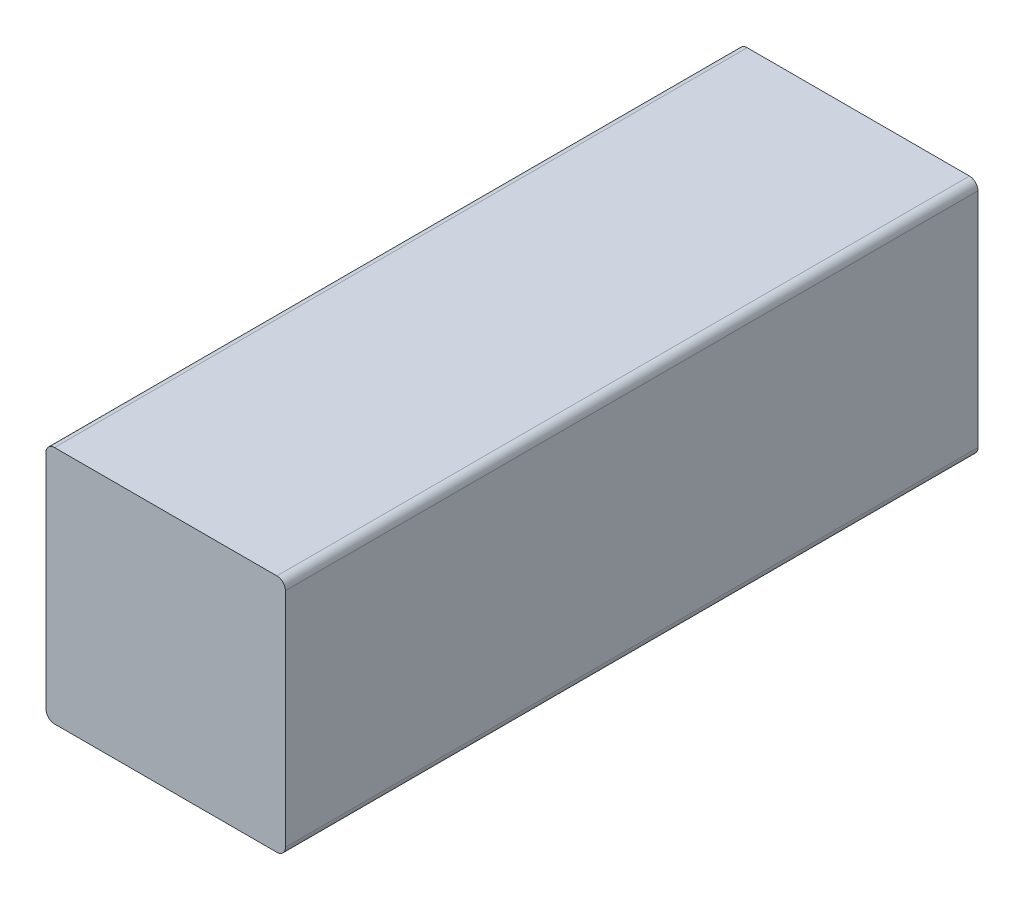
SolidWorks part; units mm, degrees
material "Pine"
ref_plane "Front Plane" through (0, 0, 0) normal (0, 0, 1) x (1, 0, 0)
ref_plane "Top Plane" through (0, 0, 0) normal (0, 1, 0) x (1, 0, 0)
ref_plane "Right Plane" through (0, 0, 0) normal (1, 0, 0) x (0, 0, -1)
sketch "Sketch1" plane through (0, 0, 0) normal (0, 1, 0) x (1, 0, 0)
  line L1 (-44.45, 128.5875) -> (44.45, 128.5875)
  line L2 (-44.45, 128.5875) -> (-44.45, -128.5875)
  line L3 (-44.45, -128.5875) -> (44.45, -128.5875)
  line L4 (44.45, 128.5875) -> (44.45, -128.5875)
  line L5 (0, -128.5875) -> (0, 128.5875) construction
  line L6 (-44.45, 0) -> (44.45, 0) construction
  point P0 (0, 0)
  dimension "D1" = 88.9
  dimension "D2" = 257.175
extrude "Boss-Extrude1" add sketch "Sketch1" along normal blind 88.9
fillet "Fillet1" radius 3.175 4 edges at (-44.45, 0, 0) (-44.45, 88.9, 0) (44.45, 0, 0) (44.45, 88.9, 0)
